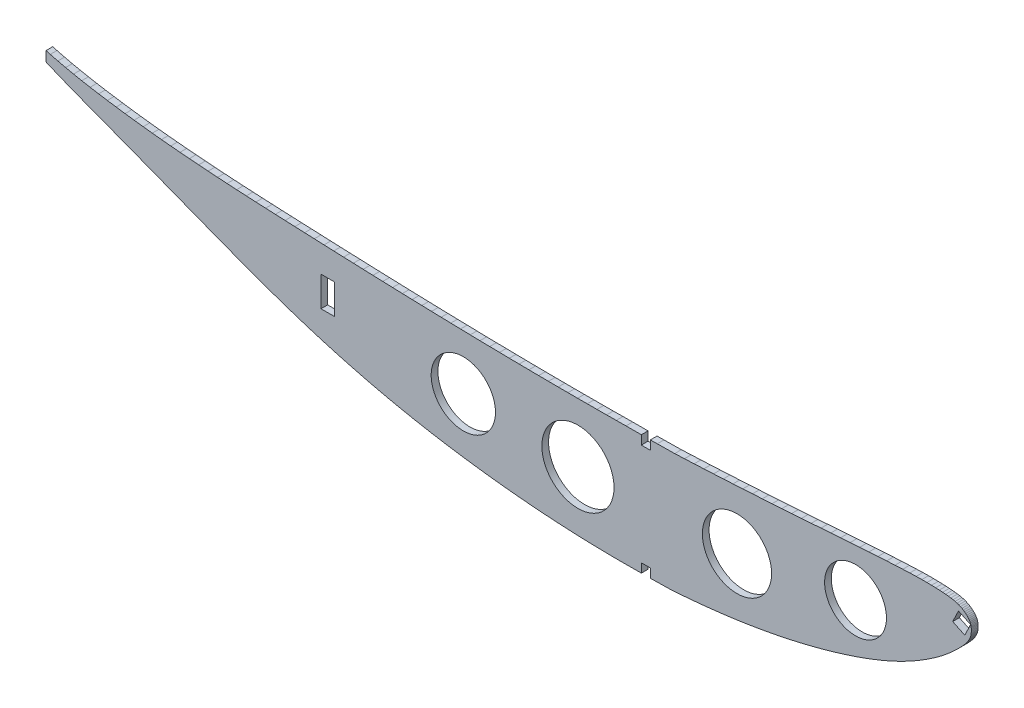
SolidWorks part; units mm, degrees
ref_plane "前视基准面" through (0, 0, 0) normal (0, 0, 1) x (1, 0, 0)
ref_plane "上视基准面" through (0, 0, 0) normal (0, 1, 0) x (1, 0, 0)
ref_plane "右视基准面" through (0, 0, 0) normal (1, 0, 0) x (0, 0, -1)
sketch "Model" plane through (0, 0, 0) normal (0, 0, 1) x (1, 0, 0)
  line L0 (151.2985, 85.5627) -> (152.3481, 85.1171)
  line L1 (152.3481, 85.1171) -> (154.1278, 84.381)
  line L2 (154.1278, 84.381) -> (155.967, 83.6391)
  line L3 (155.967, 83.6391) -> (157.855, 82.8963)
  line L4 (157.855, 82.8963) -> (159.7928, 82.1496)
  line L5 (159.7928, 82.1496) -> (161.7722, 81.3963)
  line L6 (161.7722, 81.3963) -> (163.7852, 80.6355)
  line L7 (163.7852, 80.6355) -> (165.8173, 79.8645)
  line L8 (165.8173, 79.8645) -> (167.8603, 79.0885)
  line L9 (167.8603, 79.0885) -> (169.9073, 78.3067)
  line L10 (169.9073, 78.3067) -> (171.9614, 77.5196)
  line L11 (171.9614, 77.5196) -> (174.016, 76.7306)
  line L12 (174.016, 76.7306) -> (176.0687, 75.9392)
  line L13 (176.0687, 75.9392) -> (178.1207, 75.1473)
  line L14 (178.1207, 75.1473) -> (180.1654, 74.3576)
  line L15 (180.1654, 74.3576) -> (182.1985, 73.5705)
  line L16 (182.1985, 73.5705) -> (184.2233, 72.7887)
  line L17 (184.2233, 72.7887) -> (186.245, 72.0071)
  line L18 (186.245, 72.0071) -> (188.2686, 71.2266)
  line L19 (188.2686, 71.2266) -> (190.2942, 70.4497)
  line L20 (190.2942, 70.4497) -> (192.3116, 69.6801)
  line L21 (192.3116, 69.6801) -> (194.3192, 68.9215)
  line L22 (194.3192, 68.9215) -> (196.315, 68.1752)
  line L23 (196.315, 68.1752) -> (198.2952, 67.4465)
  line L24 (198.2952, 67.4465) -> (200.2688, 66.7343)
  line L25 (200.2688, 66.7343) -> (202.2316, 66.038)
  line L26 (202.2316, 66.038) -> (204.1826, 65.3622)
  line L27 (204.1826, 65.3622) -> (206.1298, 64.7076)
  line L28 (206.1298, 64.7076) -> (208.0748, 64.0692)
  line L29 (208.0748, 64.0692) -> (210.0143, 63.4539)
  line L30 (210.0143, 63.4539) -> (211.9591, 62.8562)
  line L31 (211.9591, 62.8562) -> (213.9042, 62.2764)
  line L32 (213.9042, 62.2764) -> (215.8505, 61.7169)
  line L33 (215.8505, 61.7169) -> (217.8015, 61.1763)
  line L34 (217.8015, 61.1763) -> (219.7578, 60.6533)
  line L35 (219.7578, 60.6533) -> (221.7152, 60.1488)
  line L36 (221.7152, 60.1488) -> (223.6767, 59.6645)
  line L37 (223.6767, 59.6645) -> (225.6429, 59.1971)
  line L38 (225.6429, 59.1971) -> (227.6127, 58.7506)
  line L39 (227.6127, 58.7506) -> (229.5877, 58.321)
  line L40 (229.5877, 58.321) -> (231.5682, 57.9116)
  line L41 (231.5682, 57.9116) -> (233.5559, 57.5196)
  line L42 (233.5559, 57.5196) -> (235.5507, 57.1458)
  line L43 (235.5507, 57.1458) -> (237.5513, 56.7877)
  line L44 (237.5513, 56.7877) -> (239.5555, 56.4492)
  line L45 (239.5555, 56.4492) -> (241.5686, 56.1274)
  line L46 (241.5686, 56.1274) -> (243.5907, 55.8225)
  line L47 (243.5907, 55.8225) -> (245.6173, 55.5321)
  line L48 (245.6173, 55.5321) -> (247.6491, 55.2588)
  line L49 (247.6491, 55.2588) -> (249.6842, 55)
  line L50 (249.6842, 55) -> (251.7228, 54.759)
  line L51 (251.7228, 54.759) -> (253.7634, 54.5327)
  line L52 (253.7634, 54.5327) -> (255.8062, 54.3236)
  line L53 (255.8062, 54.3236) -> (257.8511, 54.1298)
  line L54 (257.8511, 54.1298) -> (259.8939, 53.9534)
  line L55 (259.8939, 53.9534) -> (261.9401, 53.7941)
  line L56 (261.9401, 53.7941) -> (263.9864, 53.6489)
  line L57 (263.9864, 53.6489) -> (266.0307, 53.5225)
  line L58 (266.0307, 53.5225) -> (268.0777, 53.4125)
  line L59 (268.0777, 53.4125) -> (270.122, 53.3181)
  line L60 (270.122, 53.3181) -> (272.1648, 53.243)
  line L61 (272.1648, 53.243) -> (274.2096, 53.1832)
  line L62 (274.2096, 53.1832) -> (276.2481, 53.141)
  line L63 (276.2481, 53.141) -> (278.2882, 53.1185)
  line L64 (278.2882, 53.1185) -> (280.3261, 53.1109)
  line L65 (280.3261, 53.1109) -> (282.3595, 53.1227)
  line L66 (286.4507, 53.1438) -> (291.025, 53.2234)
  line L67 (291.025, 53.2234) -> (293.0381, 53.3678)
  line L68 (293.0381, 53.3678) -> (295.0482, 53.532)
  line L69 (295.0482, 53.532) -> (297.0527, 53.7131)
  line L70 (297.0527, 53.7131) -> (299.0481, 53.9143)
  line L71 (299.0481, 53.9143) -> (301.0373, 54.1354)
  line L72 (301.0373, 54.1354) -> (303.0162, 54.3753)
  line L73 (303.0162, 54.3753) -> (304.9865, 54.6372)
  line L74 (304.9865, 54.6372) -> (306.9483, 54.9197)
  line L75 (306.9483, 54.9197) -> (308.9003, 55.2236)
  line L76 (308.9003, 55.2236) -> (310.8439, 55.5493)
  line L77 (310.8439, 55.5493) -> (312.7771, 55.897)
  line L78 (312.7771, 55.897) -> (314.7025, 56.2671)
  line L79 (314.7025, 56.2671) -> (316.6144, 56.6581)
  line L80 (316.6144, 56.6581) -> (318.5167, 57.0741)
  line L81 (318.5167, 57.0741) -> (320.4067, 57.5115)
  line L82 (320.4067, 57.5115) -> (322.2841, 57.9722)
  line L83 (322.2841, 57.9722) -> (324.1461, 58.4544)
  line L84 (324.1461, 58.4544) -> (325.9917, 58.9593)
  line L85 (325.9917, 58.9593) -> (327.8119, 59.4824)
  line L86 (327.8119, 59.4824) -> (329.6065, 60.0293)
  line L87 (329.6065, 60.0293) -> (331.3734, 60.5956)
  line L88 (331.3734, 60.5956) -> (333.1059, 61.1847)
  line L89 (333.1059, 61.1847) -> (334.8046, 61.7935)
  line L90 (334.8046, 61.7935) -> (336.4607, 62.4217)
  line L91 (336.4607, 62.4217) -> (338.0732, 63.0705)
  line L92 (338.0732, 63.0705) -> (339.6375, 63.7377)
  line L93 (339.6375, 63.7377) -> (341.1469, 64.4197)
  line L94 (341.1469, 64.4197) -> (342.5965, 65.1224)
  line L95 (342.5965, 65.1224) -> (343.9905, 65.8405)
  line L96 (343.9905, 65.8405) -> (345.3201, 66.5689)
  line L97 (345.3201, 66.5689) -> (346.5807, 67.301)
  line L98 (346.5807, 67.301) -> (347.7654, 68.0295)
  line L99 (347.7654, 68.0295) -> (348.8681, 68.7437)
  line L100 (348.8681, 68.7437) -> (349.883, 69.4349)
  line L101 (349.883, 69.4349) -> (350.8074, 70.0961)
  line L102 (350.8074, 70.0961) -> (351.6425, 70.7258)
  line L103 (351.6425, 70.7258) -> (352.3949, 71.3201)
  line L104 (352.3949, 71.3201) -> (353.0695, 71.8777)
  line L105 (353.0695, 71.8777) -> (353.6733, 72.402)
  line L106 (353.6733, 72.402) -> (354.2148, 72.8926)
  line L107 (354.2148, 72.8926) -> (354.7021, 73.3494)
  line L108 (354.7021, 73.3494) -> (355.1408, 73.7758)
  line L109 (355.1408, 73.7758) -> (355.5384, 74.1728)
  line L110 (355.5384, 74.1728) -> (355.8998, 74.5427)
  line L111 (355.8998, 74.5427) -> (356.229, 74.8884)
  line L112 (356.229, 74.8884) -> (356.526, 75.2148)
  line L113 (356.526, 75.2148) -> (356.7954, 75.5262)
  line L114 (356.7954, 75.5262) -> (357.0378, 75.8243)
  line L115 (357.0378, 75.8243) -> (357.2551, 76.1123)
  line L116 (357.2551, 76.1123) -> (357.4505, 76.3905)
  line L117 (357.4505, 76.3905) -> (357.6247, 76.6607)
  line L118 (357.6247, 76.6607) -> (357.7758, 76.9251)
  line L119 (357.7758, 76.9251) -> (357.9051, 77.1846)
  line L120 (357.9051, 77.1846) -> (358.0152, 77.4386)
  line L121 (358.0152, 77.4386) -> (358.1017, 77.6891)
  line L122 (358.1017, 77.6891) -> (358.1652, 77.9362)
  line L123 (358.1652, 77.9362) -> (358.2082, 78.1777)
  line L124 (358.2082, 78.1777) -> (358.2257, 78.414)
  line L125 (358.2394, 79.2892) -> (358.2292, 79.5268)
  line L126 (358.2292, 79.5268) -> (358.205, 79.7674)
  line L127 (358.205, 79.7674) -> (358.1418, 80.0083)
  line L128 (358.1418, 80.0083) -> (358.0515, 80.2471)
  line L129 (358.0515, 80.2471) -> (357.9344, 80.4826)
  line L130 (357.9344, 80.4826) -> (357.7914, 80.7134)
  line L131 (357.7914, 80.7134) -> (357.6246, 80.9388)
  line L132 (357.6246, 80.9388) -> (357.4356, 81.1601)
  line L133 (357.4356, 81.1601) -> (357.2234, 81.3748)
  line L134 (357.2234, 81.3748) -> (356.9889, 81.5828)
  line L135 (356.9889, 81.5828) -> (356.7332, 81.7873)
  line L136 (356.7332, 81.7873) -> (356.4531, 81.981)
  line L137 (356.4531, 81.981) -> (356.1468, 82.1656)
  line L138 (356.1468, 82.1656) -> (355.8154, 82.3394)
  line L139 (355.8154, 82.3394) -> (355.4545, 82.4983)
  line L140 (355.4545, 82.4983) -> (355.0614, 82.6354)
  line L141 (355.0614, 82.6354) -> (354.6337, 82.7558)
  line L142 (354.6337, 82.7558) -> (354.1696, 82.8553)
  line L143 (354.1696, 82.8553) -> (353.6628, 82.9359)
  line L144 (353.6628, 82.9359) -> (353.1087, 83.004)
  line L145 (353.1087, 83.004) -> (352.5007, 83.0629)
  line L146 (352.5007, 83.0629) -> (351.8302, 83.119)
  line L147 (351.8302, 83.119) -> (351.0892, 83.1695)
  line L148 (351.0892, 83.1695) -> (350.2658, 83.2094)
  line L149 (350.2658, 83.2094) -> (349.3483, 83.2408)
  line L150 (349.3483, 83.2408) -> (348.3248, 83.2574)
  line L151 (348.3248, 83.2574) -> (347.1816, 83.256)
  line L152 (347.1816, 83.256) -> (345.9069, 83.2333)
  line L153 (345.9069, 83.2333) -> (344.4838, 83.1849)
  line L154 (344.4838, 83.1849) -> (342.907, 83.1166)
  line L155 (342.907, 83.1166) -> (341.1785, 83.0301)
  line L156 (341.1785, 83.0301) -> (339.325, 82.9326)
  line L157 (339.325, 82.9326) -> (337.3741, 82.8218)
  line L158 (337.3741, 82.8218) -> (335.3556, 82.6992)
  line L159 (335.3556, 82.6992) -> (333.2804, 82.5613)
  line L160 (333.2804, 82.5613) -> (331.1605, 82.4151)
  line L161 (331.1605, 82.4151) -> (329.007, 82.2602)
  line L162 (329.007, 82.2602) -> (326.8275, 82.1031)
  line L163 (326.8275, 82.1031) -> (324.6368, 81.9445)
  line L164 (324.6368, 81.9445) -> (322.4425, 81.7874)
  line L165 (322.4425, 81.7874) -> (320.2502, 81.6332)
  line L166 (320.2502, 81.6332) -> (318.0592, 81.4827)
  line L167 (318.0592, 81.4827) -> (315.8689, 81.3358)
  line L168 (315.8689, 81.3358) -> (313.6801, 81.1927)
  line L169 (313.6801, 81.1927) -> (311.4932, 81.0537)
  line L170 (311.4932, 81.0537) -> (309.3089, 80.919)
  line L171 (309.3089, 80.919) -> (307.1303, 80.789)
  line L172 (307.1303, 80.789) -> (304.9501, 80.6647)
  line L173 (304.9501, 80.6647) -> (302.7738, 80.5439)
  line L174 (302.7738, 80.5439) -> (300.6001, 80.4298)
  line L175 (300.6001, 80.4298) -> (298.4246, 80.3182)
  line L176 (298.4246, 80.3182) -> (296.2574, 80.2119)
  line L177 (296.2574, 80.2119) -> (294.0849, 80.1132)
  line L178 (294.0849, 80.1132) -> (291.9099, 80.0158)
  line L179 (291.9099, 80.0158) -> (288.0165, 79.9641)
  line L180 (288.0165, 79.9641) -> (287.4507, 79.9531)
  line L181 (281.009, 79.9344) -> (284.4507, 79.9344)
  line L182 (281.009, 79.9344) -> (278.8417, 79.9133)
  line L183 (278.8417, 79.9133) -> (276.6765, 79.8964)
  line L184 (276.6765, 79.8964) -> (274.5184, 79.8846)
  line L185 (274.5184, 79.8846) -> (272.3557, 79.8793)
  line L186 (272.3557, 79.8793) -> (270.1919, 79.8766)
  line L187 (270.1919, 79.8766) -> (268.0204, 79.8798)
  line L188 (268.0204, 79.8798) -> (265.8485, 79.8861)
  line L189 (265.8485, 79.8861) -> (263.6695, 79.899)
  line L190 (263.6695, 79.899) -> (261.4857, 79.9159)
  line L191 (261.4857, 79.9159) -> (259.2998, 79.9372)
  line L192 (259.2998, 79.9372) -> (257.1116, 79.9629)
  line L193 (257.1116, 79.9629) -> (254.9225, 79.993)
  line L194 (254.9225, 79.993) -> (252.7298, 80.0271)
  line L195 (252.7298, 80.0271) -> (250.5405, 80.064)
  line L196 (250.5405, 80.064) -> (248.3544, 80.1051)
  line L197 (248.3544, 80.1051) -> (246.1729, 80.1508)
  line L198 (246.1729, 80.1508) -> (243.9946, 80.1995)
  line L199 (243.9946, 80.1995) -> (241.8295, 80.2517)
  line L200 (241.8295, 80.2517) -> (239.6702, 80.3074)
  line L201 (239.6702, 80.3074) -> (237.5147, 80.3659)
  line L202 (237.5147, 80.3659) -> (235.3539, 80.429)
  line L203 (235.3539, 80.429) -> (233.187, 80.4931)
  line L204 (233.187, 80.4931) -> (231.0045, 80.5643)
  line L205 (231.0045, 80.5643) -> (228.8127, 80.6365)
  line L206 (228.8127, 80.6365) -> (226.6205, 80.7131)
  line L207 (226.6205, 80.7131) -> (224.4236, 80.7931)
  line L208 (224.4236, 80.7931) -> (222.2268, 80.8742)
  line L209 (222.2268, 80.8742) -> (220.0351, 80.9595)
  line L210 (220.0351, 80.9595) -> (217.843, 81.0472)
  line L211 (217.843, 81.0472) -> (215.6546, 81.1353)
  line L212 (215.6546, 81.1353) -> (213.4762, 81.226)
  line L213 (213.4762, 81.226) -> (211.3041, 81.3187)
  line L214 (211.3041, 81.3187) -> (209.1319, 81.4103)
  line L215 (209.1319, 81.4103) -> (206.9532, 81.5065)
  line L216 (206.9532, 81.5065) -> (204.7695, 81.6024)
  line L217 (204.7695, 81.6024) -> (202.5884, 81.7013)
  line L218 (202.5884, 81.7013) -> (200.4114, 81.8048)
  line L219 (200.4114, 81.8048) -> (198.2407, 81.9117)
  line L220 (198.2407, 81.9117) -> (196.0832, 82.0235)
  line L221 (196.0832, 82.0235) -> (193.9336, 82.1434)
  line L222 (193.9336, 82.1434) -> (191.7942, 82.2696)
  line L223 (191.7942, 82.2696) -> (189.6689, 82.4048)
  line L224 (189.6689, 82.4048) -> (187.5497, 82.5503)
  line L225 (187.5497, 82.5503) -> (185.4452, 82.7048)
  line L226 (185.4452, 82.7048) -> (183.3482, 82.8712)
  line L227 (183.3482, 82.8712) -> (181.2647, 83.0493)
  line L228 (181.2647, 83.0493) -> (179.1864, 83.2412)
  line L229 (179.1864, 83.2412) -> (177.121, 83.4436)
  line L230 (177.121, 83.4436) -> (175.0681, 83.6607)
  line L231 (175.0681, 83.6607) -> (173.0278, 83.8931)
  line L232 (173.0278, 83.8931) -> (170.9952, 84.1412)
  line L233 (170.9952, 84.1412) -> (168.9805, 84.4013)
  line L234 (168.9805, 84.4013) -> (166.9853, 84.6782)
  line L235 (166.9853, 84.6782) -> (165.0094, 84.9695)
  line L236 (165.0094, 84.9695) -> (163.0652, 85.2751)
  line L237 (163.0652, 85.2751) -> (161.1552, 85.5967)
  line L238 (161.1552, 85.5967) -> (159.2893, 85.9356)
  line L239 (159.2893, 85.9356) -> (157.4624, 86.297)
  line L240 (157.4624, 86.297) -> (155.6816, 86.6782)
  line L241 (155.6816, 86.6782) -> (153.9461, 87.0846)
  line L242 (153.9461, 87.0846) -> (152.2575, 87.5125)
  line L243 (152.2575, 87.5125) -> (151.2985, 87.7741)
  line L244 (284.4507, 53.1292) -> (282.3595, 53.1227)
  line L245 (356.7895, 77.2748) -> (354.0834, 78.5697)
  line L246 (354.0834, 78.5697) -> (355.3782, 81.2758)
  line L247 (355.3782, 81.2758) -> (358.0844, 79.981)
  line L248 (358.0844, 79.981) -> (356.7895, 77.2748)
  line L249 (286.4507, 53.1438) -> (286.4507, 55.1438)
  line L250 (286.4507, 55.1438) -> (284.4507, 55.1438)
  line L251 (284.4507, 55.1438) -> (284.4507, 53.1292)
  line L252 (284.4507, 79.9344) -> (284.4507, 77.9344)
  line L253 (284.4507, 77.9344) -> (286.4507, 77.9344)
  line L254 (286.4507, 79.9336) -> (286.4507, 77.9344)
  line L255 (215.8191, 75.2157) -> (212.8039, 75.2157)
  line L256 (215.8191, 68.5152) -> (212.8039, 68.5152)
  line L257 (212.8039, 68.5152) -> (212.8039, 75.2157)
  line L258 (215.8191, 75.2157) -> (215.8191, 68.5152)
  line L259 (358.2394, 79.2892) -> (358.2426, 79)
  line L260 (358.2426, 79) -> (358.2441, 78.7275)
  line L261 (358.2441, 78.7275) -> (358.2257, 78.414)
  line L262 (151.2985, 87.7741) -> (151.2985, 85.5627)
  line L263 (287.4507, 79.9531) -> (286.4507, 79.9336)
  circle A0 centre (332.3539, 71.8503) radius 6.9172
  circle A1 centre (305.8385, 67.5993) radius 7.7414
  circle A2 centre (270.2682, 66.6423) radius 8.0721
  circle A3 centre (244.6354, 67.9583) radius 7.1885
extrude "凸台-拉伸1" add sketch "Model" along normal blind 1.5
